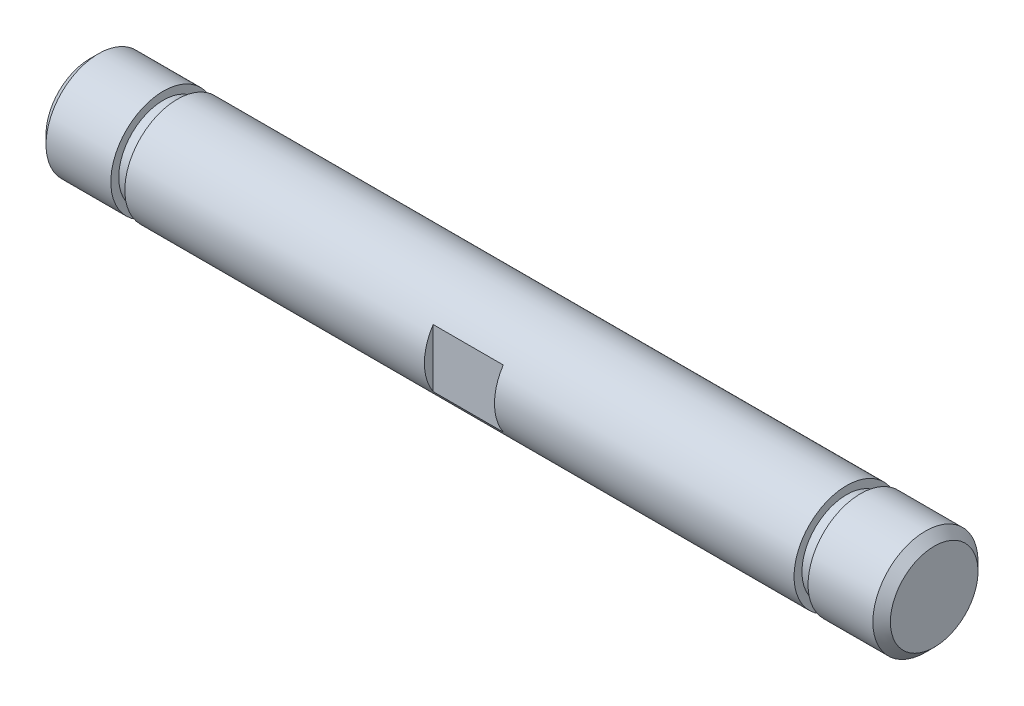
SolidWorks part; units mm, degrees
ref_plane "Alzado" through (0, 0, 0) normal (1, 0, 0) x (0, 1, 0)
ref_plane "Planta" through (0, 0, 0) normal (0, 0, 1) x (0, 1, 0)
ref_plane "Vista lateral" through (0, 0, 0) normal (0, 1, 0) x (-1, 0, 0)
sketch "Croquis1" plane through (0, 0, 0) normal (0, 1, 0) x (-1, 0, 0)
  line L1 (-19.1, 3) -> (19.1, 3)
  line L6 (24.1, 3) -> (24.1, 0)
  line L7 (-24.1, 0) -> (24.1, 0) construction
  line L22 (-24.1, 0) -> (24.1, 0)
  line L23 (19.1, 3) -> (19.1, 2.55)
  line L24 (19.1, 2.55) -> (19.9, 2.55)
  line L25 (19.9, 2.55) -> (19.9, 3)
  line L26 (19.9, 3) -> (24.1, 3)
  line L27 (0, 0) -> (0, 3) construction
  line L28 (-19.9, 3) -> (-24.1, 3)
  line L29 (-19.9, 2.55) -> (-19.9, 3)
  line L30 (-19.1, 2.55) -> (-19.9, 2.55)
  line L31 (-19.1, 3) -> (-19.1, 2.55)
  line L32 (-24.1, 3) -> (-24.1, 0)
  dimension "D1" = 5
  dimension "D2" = 6
  dimension "D3" = 38.2
  dimension "D4" = 0.8
  dimension "D7" = 0.45
revolve "Revolución1" add sketch "Croquis1" angle 360 about L7
sketch "Croquis2" plane through (0, 0, 0) normal (1, 0, 0) x (0, 1, 0)
  line L1 (1.6583, 2.5) -> (-1.6583, 2.5)
  circle A0 centre (0, 0) radius 3 construction
  circle A1 centre (0, 0) radius 3
  arc A3 (1.6583, 2.5) -> (-1.6583, 2.5) centre (0, 0) ccw
  point P4 (0, 3)
  dimension "D2" = 0.5
  dimension "D1" = 0
extrude "Cortar-Extruir1" cut sketch "Croquis2" against normal mid plane 4
chamfer "Chaflán1" distance 0.5 angle 45 2 edges at (-24.1, 0, -3) (24.1, 0, -3)
equation "\"ancho_circlip\"=0.8"
equation "\"ranura_circlip\"=0.45"
